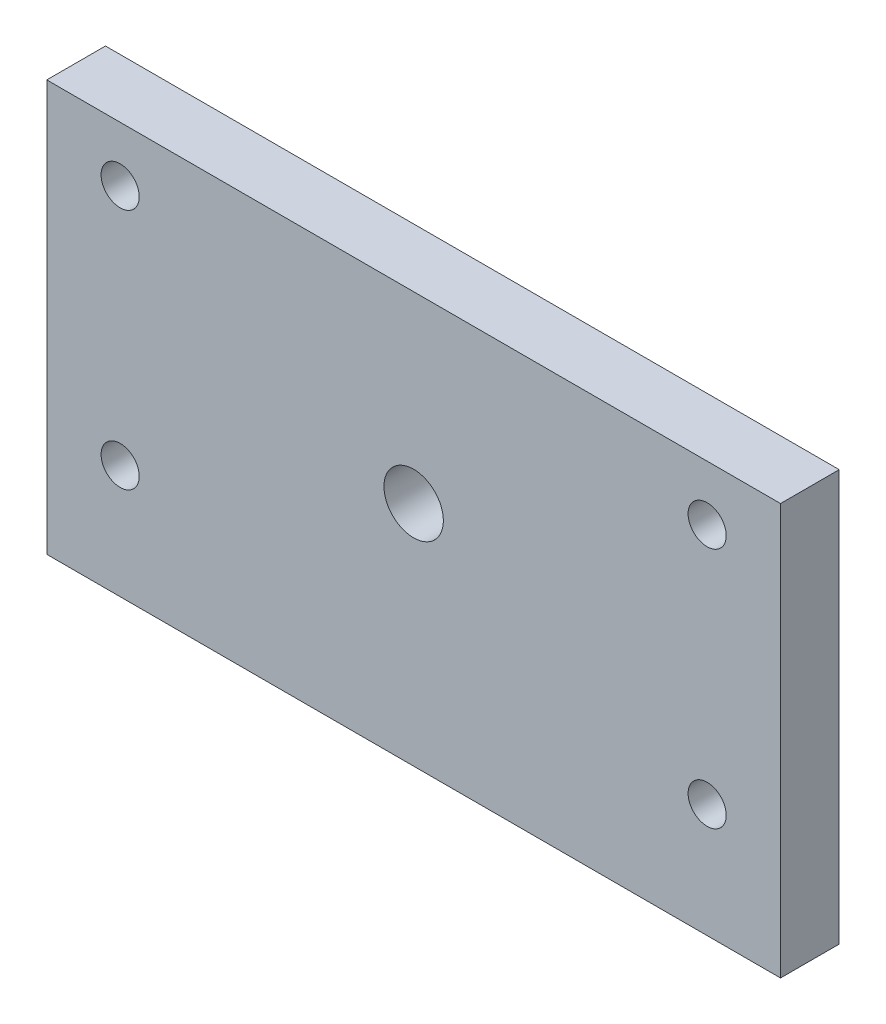
SolidWorks part; units mm, degrees
ref_plane "Ön Düzlem" through (0, 0, 0) normal (0, 0, 1) x (1, 0, 0)
ref_plane "Üst Düzlem" through (0, 0, 0) normal (0, 1, 0) x (1, 0, 0)
ref_plane "Sağ Düzlem" through (0, 0, 0) normal (1, 0, 0) x (0, 0, -1)
sketch "Çizim1" plane through (0, 0, 0) normal (0, 0, 1) x (1, 0, 0)
  line L1 (-42.6221, 26.9702) -> (57.3779, 26.9702)
  line L2 (-42.6221, 26.9702) -> (-42.6221, -29.0298)
  line L3 (-42.6221, -29.0298) -> (57.3779, -29.0298)
  line L4 (57.3779, 26.9702) -> (57.3779, -29.0298)
  circle A0 centre (7.3779, 1.9702) radius 4.05
  dimension "D3" = 25
  dimension "D4" = 8.1
  dimension "D1" = 100
  dimension "D2" = 56
extrude "Yükseklik-Ekstrüzyon1" add sketch "Çizim1" along normal blind 8
sketch "Çizim3" plane through (0, 0, 8) normal (0, 0, 1) x (1, 0, 0)
  circle A0 centre (-32.6221, 19.4702) radius 2.6
  circle A1 centre (47.3779, 19.4702) radius 2.6
  circle A2 centre (47.3779, -13.5298) radius 2.6
  circle A3 centre (-32.6221, -13.5298) radius 2.6
extrude "Kes-Ekstrüzyon2" cut sketch "Çizim3" against normal blind 10
